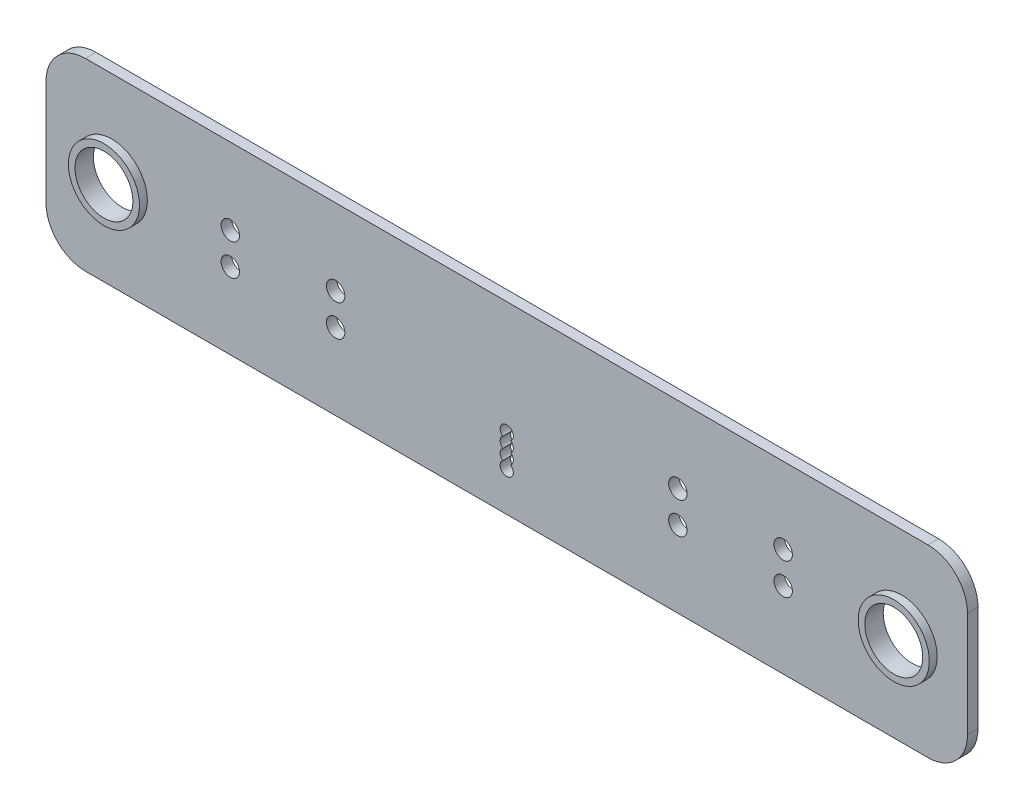
SolidWorks part; units mm, degrees
ref_plane "Ön Düzlem" through (0, 0, 0) normal (0, 0, 1) x (1, 0, 0)
ref_plane "Üst Düzlem" through (0, 0, 0) normal (0, 1, 0) x (1, 0, 0)
ref_plane "Sağ Düzlem" through (0, 0, 0) normal (1, 0, 0) x (0, 0, -1)
sketch "Sketch1" plane through (0, 0, 0) normal (0, 0, 1) x (1, 0, 0)
  line L1 (-175, 35) -> (175, 35)
  line L2 (-175, 35) -> (-175, -35)
  line L3 (-175, -35) -> (175, -35)
  line L4 (175, 35) -> (175, -35)
  line L5 (-175, 35) -> (175, -35) construction
  line L6 (-175, -35) -> (175, 35) construction
  point P0 (0, 0)
  dimension "D1" = 70
  dimension "D2" = 350
extrude "Boss-Extrude1" add sketch "Sketch1" along normal blind 4
fillet "Fillet1" radius 15 4 edges at (175, -35, 2) (175, 35, 2) (-175, -35, 2) (-175, 35, 2)
sketch "Sketch2" plane through (0, 0, 0) normal (0, 0, -1) x (-1, 0, 0)
  line L0 (-175, -20) -> (-175, 20) construction
  circle A0 centre (-150, 0) radius 11
  dimension "D1" = 25
  dimension "D2" = 22
extrude "Cut-Extrude1" cut sketch "Sketch2" against normal blind 10
sketch "Sketch3" plane through (0, 0, 0) normal (0, 0, -1) x (-1, 0, 0)
  circle A0 centre (-150, 0) radius 15
  circle A1 centre (-150, 0) radius 17.5
  dimension "D1" = 35
  dimension "D2" = 30
extrude "Boss-Extrude2" add sketch "Sketch3" along normal blind 6
mirror "Mirror2" about plane through (0, 0, 0) normal (1, 0, 0) of "Cut-Extrude1", "Boss-Extrude2"
sketch "Sketch4" plane through (0, 0, 4) normal (0, 0, 1) x (1, 0, 0)
  circle A6 centre (-105, 6) radius 3.5
  circle A7 centre (-105, -6) radius 3.5
  circle A8 centre (-65, -6) radius 3.5
  circle A9 centre (-65, 6) radius 3.5
  circle A10 centre (65, 6) radius 3.5
  circle A11 centre (65, -6) radius 3.5
  circle A12 centre (105, -6) radius 3.5
  circle A13 centre (105, 6) radius 3.5
  circle A14 centre (150, 0) radius 11 construction
  circle A15 centre (-150, 0) radius 11 construction
  arc A16 (-1.5, -14) -> (-1.5, -10) centre (0, -12) cw
  arc A17 (1.5, -14) -> (1.5, -18) centre (0, -16) cw
  arc A18 (-1.5, -10) -> (1.5, -10) centre (0, -8) cw
  arc A19 (1.5, -10) -> (1.5, -14) centre (0, -12) cw
  arc A20 (-1.5, -18) -> (-1.5, -14) centre (0, -16) cw
  arc A21 (1.5, -18) -> (-1.5, -18) centre (0, -20) cw
  dimension "D4" = 12
  dimension "D5" = 12
  dimension "D6" = 12
  dimension "D2" = 12
  dimension "D7" = 6
  dimension "D8" = 6
  dimension "D9" = 45
  dimension "D10" = 40
  dimension "D11" = 6
  dimension "D12" = 45
  dimension "D13" = 40
extrude "Cut-Extrude3" cut sketch "Sketch4" against normal blind 10
sketch "Sketch5" plane through (0, 35, 0) normal (0, 1, 0) x (1, 0, 0)
  line L0 (-175, 0) -> (175, 0)
  line L1 (-175, 0) -> (-175, 21.2346)
  line L2 (175, 0) -> (175, 21.2346)
  line L3 (-175, 21.2346) -> (175, 21.2346)
extrude "Cut-Extrude4" cut sketch "Sketch5" against normal blind 142
sketch "Sketch6" plane through (0, 0, 4) normal (0, 0, 1) x (1, 0, 0)
  circle A0 centre (-150, 0) radius 13.5
  circle A1 centre (150, 0) radius 13.5
  circle A2 centre (-150, 0) radius 11
  circle A3 centre (150, 0) radius 11
  dimension "D1" = 27
  dimension "D2" = 27
  dimension "D3" = 22
  dimension "D4" = 22
extrude "Boss-Extrude3" add sketch "Sketch6" along normal blind 3
